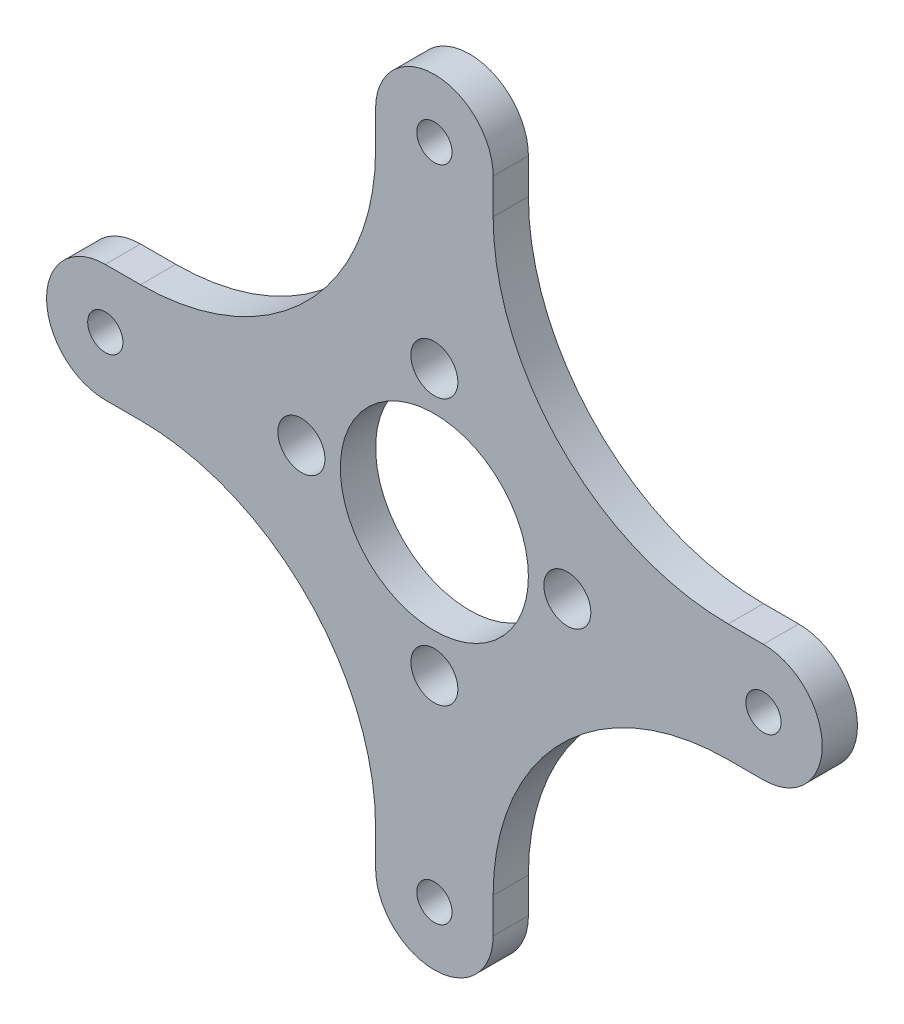
SolidWorks part; units mm, degrees
material "PLA Density Only"
ref_plane "Front Plane" through (0, 0, 0) normal (0, 0, 1) x (1, 0, 0)
ref_plane "Top Plane" through (0, 0, 0) normal (0, 1, 0) x (1, 0, 0)
ref_plane "Right Plane" through (0, 0, 0) normal (1, 0, 0) x (0, 0, -1)
sketch "Sketch1" plane through (0, 0, 0) normal (0, 0, 1) x (1, 0, 0)
  line L4 (0, 28) -> (0, -11.3137) construction
  line L5 (5, 28) -> (5, 25)
  line L6 (-5, 28) -> (-5, 25)
  line L7 (28, 5) -> (25, 5)
  line L8 (28, -5) -> (25, -5)
  line L9 (5, -28) -> (5, -25)
  line L10 (-5, -28) -> (-5, -25)
  line L11 (-28, -5) -> (-25, -5)
  line L12 (-28, 5) -> (-25, 5)
  circle A0 centre (0, 28) radius 1.5
  circle A1 centre (28, 0) radius 1.5
  circle A2 centre (0, -28) radius 1.5
  circle A3 centre (-28, 0) radius 1.5
  arc A4 (5, 28) -> (-5, 28) centre (0, 28) ccw
  arc A6 (28, -5) -> (28, 5) centre (28, 0) ccw
  arc A7 (-5, -28) -> (5, -28) centre (0, -28) ccw
  arc A8 (-28, 5) -> (-28, -5) centre (-28, 0) ccw
  arc A9 (-5, -25) -> (-25, -5) centre (-25, -25) ccw
  arc A10 (25, -5) -> (5, -25) centre (25, -25) ccw
  arc A11 (25, 5) -> (5, 25) centre (25, 25) cw
  arc A12 (-5, 25) -> (-25, 5) centre (-25, 25) cw
  circle A13 centre (0, -11.3137) radius 2
  circle A14 centre (-11.3137, 0) radius 2
  circle A15 centre (0, 11.3137) radius 2
  circle A16 centre (11.3137, 0) radius 2
  circle A17 centre (0, 0) radius 8
  point P4 (0, 38)
  point P12 (0, 0)
  point P45 (0, 0)
  dimension "D1" = 3
  dimension "D4" = 20
  dimension "D6" = 5
  dimension "D7" = 4
  dimension "D8" = 16
  dimension "D2" = 28
  dimension "D3" = 16
  dimension "D5" = 4
extrude "Boss-Extrude1" add sketch "Sketch1" along normal blind 3
